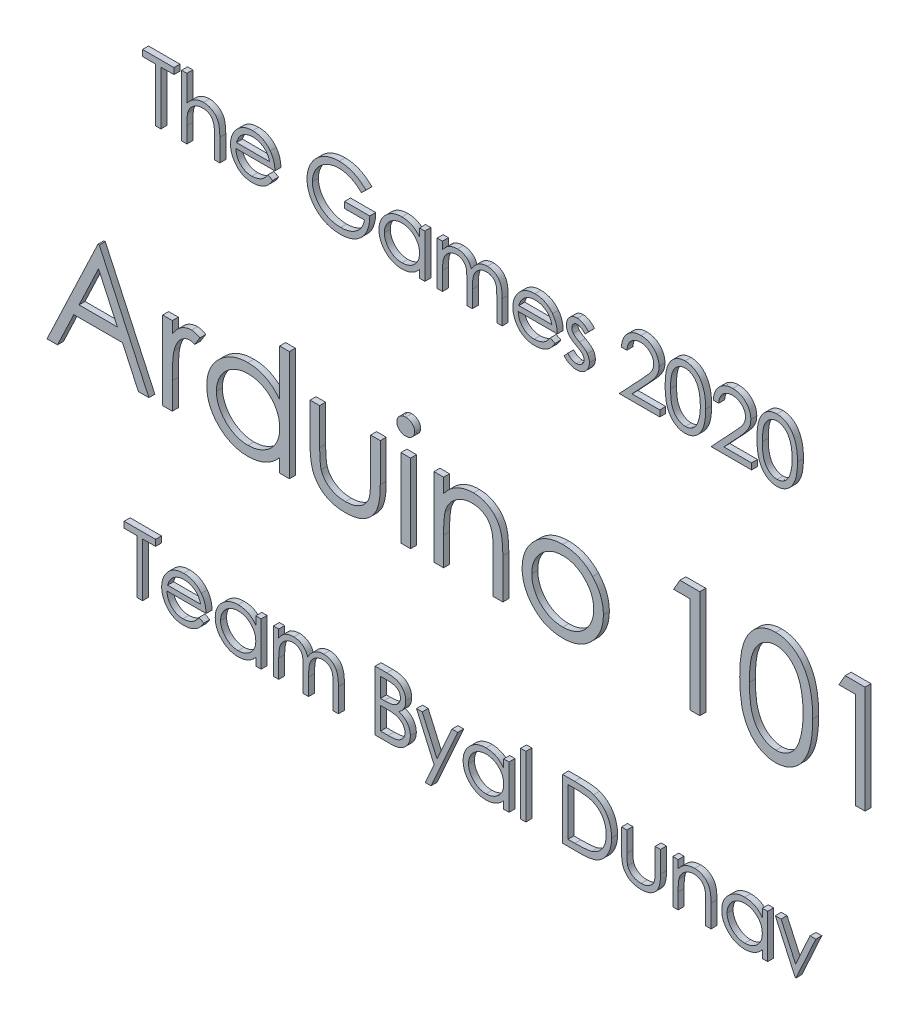
SolidWorks part; units mm, degrees
ref_plane "Front Plane" through (0, 0, 0) normal (0, 0, 1) x (1, 0, 0)
ref_plane "Top Plane" through (0, 0, 0) normal (0, 1, 0) x (1, 0, 0)
ref_plane "Right Plane" through (0, 0, 0) normal (1, 0, 0) x (0, 0, -1)
sketch "Sketch1" plane through (0, 0, 0) normal (0, 0, 1) x (1, 0, 0)
  line L0 (-425, -200) -> (425, -200) construction
  line L4 (-425, 150) -> (425, 150) construction
  line L6 (-425, -50) -> (425, -50) construction
  text T0 "The Games 2020\r\n" font "Century Gothic" height 50
  text T1 "Arduino 101" font "Century Gothic" height 90
  text T2 "Team Byal Dunav" font "Century Gothic" height 50
extrude "Boss-Extrude1" add sketch "Sketch1" along normal blind 5
